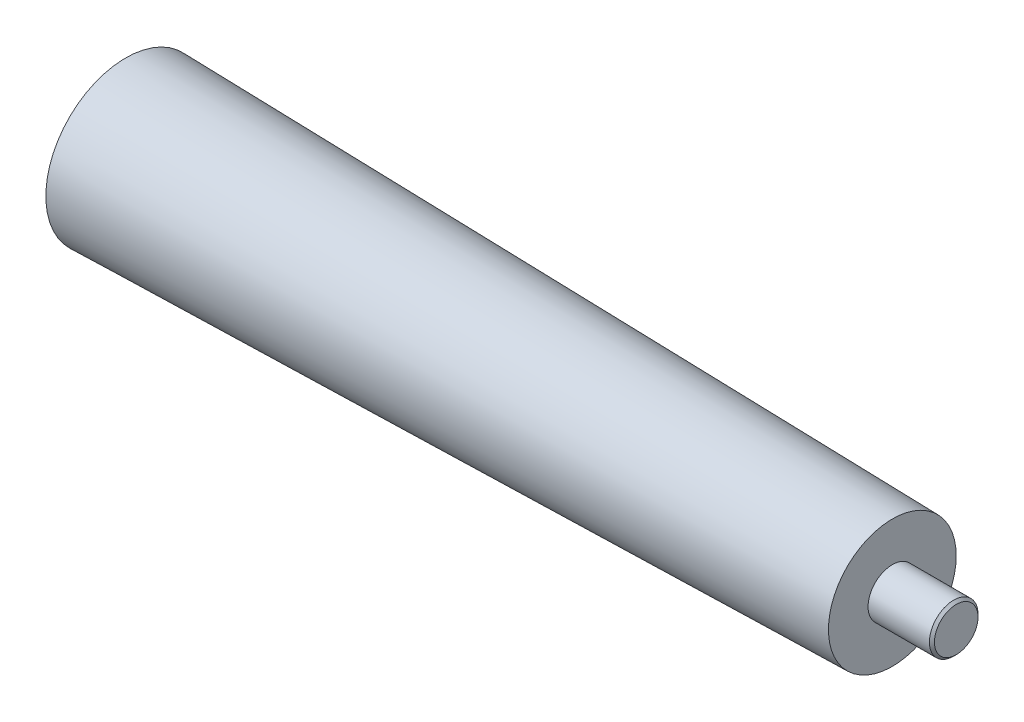
SolidWorks part; units mm, degrees
ref_plane "Front Plane" through (0, 0, 0) normal (0, 0, 1) x (1, 0, 0)
ref_plane "Top Plane" through (0, 0, 0) normal (0, 1, 0) x (1, 0, 0)
ref_plane "Right Plane" through (0, 0, 0) normal (1, 0, 0) x (0, 0, -1)
sketch "Sketch1" plane through (0, 0, 0) normal (0, 0, 1) x (1, 0, 0)
  line L0 (-82.55, 0) -> (-82.55, 15.88)
  line L1 (-82.55, 15.88) -> (69.85, 12.7)
  line L2 (69.85, 12.7) -> (69.85, 4.83)
  line L3 (69.85, 4.83) -> (82.05, 4.83)
  line L4 (82.55, 4.33) -> (82.55, 0)
  line L5 (82.55, 0) -> (-82.55, 0)
  line L6 (82.05, 4.83) -> (82.55, 4.33)
  point P5 (82.55, 4.83)
  dimension "D1" = 165.1
  dimension "D2" = 15.88
  dimension "D3" = 4.83
  dimension "D4" = 12.7
  dimension "D5" = 12.7
  dimension "D6" = 0.5
  dimension "D7" = 45
revolve "Revolve1" add sketch "Sketch1" angle 360 about L5
